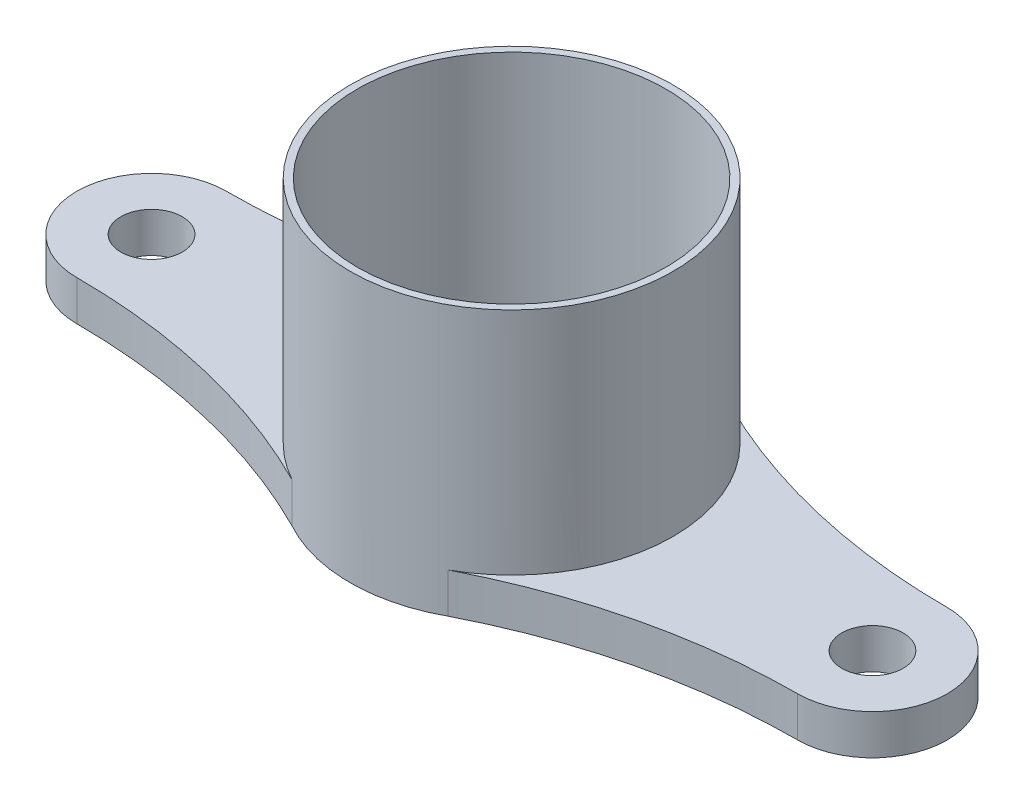
SolidWorks part; units mm, degrees
ref_plane "Front Plane" through (0, 0, 0) normal (0, 0, 1) x (1, 0, 0)
ref_plane "Top Plane" through (0, 0, 0) normal (0, 1, 0) x (1, 0, 0)
ref_plane "Right Plane" through (0, 0, 0) normal (1, 0, 0) x (0, 0, -1)
sketch "Sketch1" plane through (0, 0, 0) normal (0, 1, 0) x (1, 0, 0)
  circle A0 centre (0, 0) radius 2.85
  circle A5 centre (-13.5176, 0.032) radius 1.15
  circle A6 centre (13.4824, 0.032) radius 1.15
  arc A7 (13.4824, -2.768) -> (13.4824, 2.832) centre (13.4824, 0.032) ccw
  arc A8 (-13.5176, 2.832) -> (-13.5176, -2.768) centre (-13.5176, 0.032) ccw
  circle A9 centre (0, 0) radius 6.05
  arc A10 (-13.5176, 2.832) -> (-2.923, 5.297) centre (-13.5176, 26.832) ccw
  arc A11 (-13.5176, -2.768) -> (-2.923, -5.297) centre (-13.5176, -26.2244) cw
  arc A12 (13.4824, 2.832) -> (2.923, 5.297) centre (13.4824, 26.6806) cw
  arc A13 (13.4824, -2.768) -> (2.923, -5.297) centre (13.4824, -26.0768) ccw
  point P7 (0, 0)
  dimension "D1" = 5.7
  dimension "D2" = 2.3
  dimension "D3" = 2.3
  dimension "D4" = 5.6
  dimension "D5" = 5.6
  dimension "D6" = 12.1
  dimension "D7" = 24
extrude "Boss-Extrude1" add sketch "Sketch1" along normal blind 1.5 contours A8 A11 A9 A10 A5 | A9 A0 | A13 A7 A12 A9 A6
sketch "Sketch3" plane through (0, 0, 0) normal (0, 1, 0) x (1, 0, 0)
  circle A0 centre (0, 0) radius 6.05
  circle A1 centre (0, 0) radius 5.7819
  dimension "D1" = 12.1
extrude "Boss-Extrude6" add sketch "Sketch3" along normal blind 10.1
